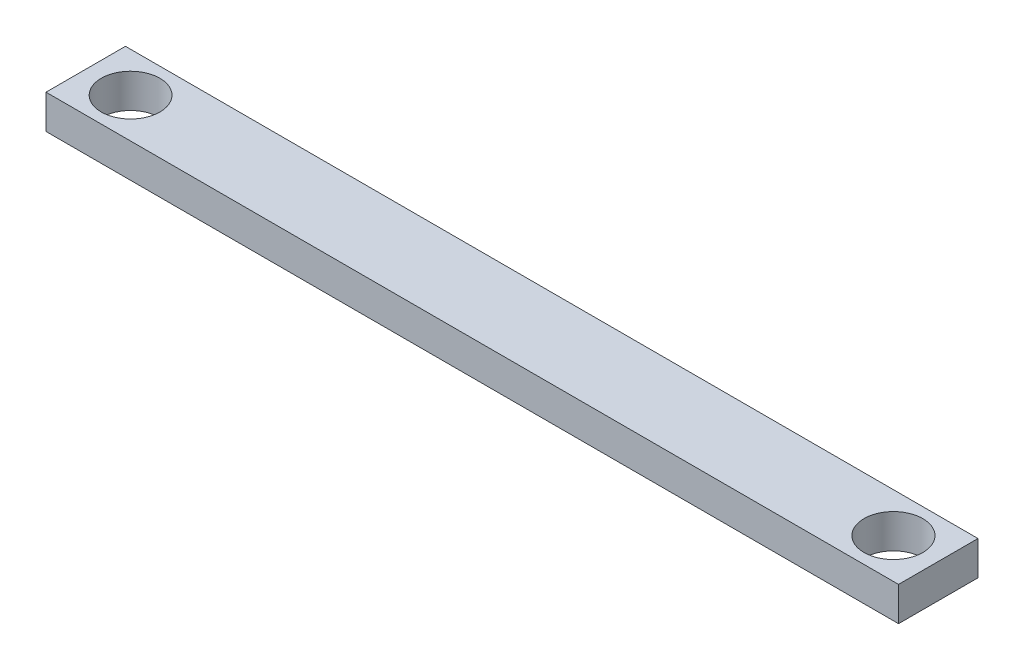
SolidWorks part; units mm, degrees
ref_plane "Front Plane" through (0, 0, 0) normal (0, 0, 1) x (1, 0, 0)
ref_plane "Top Plane" through (0, 0, 0) normal (0, 1, 0) x (1, 0, 0)
ref_plane "Right Plane" through (0, 0, 0) normal (1, 0, 0) x (0, 0, -1)
sketch "Sketch1" plane through (0, 0, 0) normal (0, 1, 0) x (1, 0, 0)
  line L0 (-47.6, 1) -> (27.5, 1) construction
  line L1 (-47.6, -2.5) -> (27.5, -2.5)
  line L2 (-47.6, -2.5) -> (-47.6, 4.5)
  line L3 (-47.6, 4.5) -> (27.5, 4.5)
  line L4 (27.5, -2.5) -> (27.5, 4.5)
  line L7 (-10.05, 4.5) -> (-10.05, -2.5) construction
  line L8 (-43.65, 4.5) -> (-43.65, -2.5) construction
  line L9 (23.55, 4.5) -> (23.55, -2.5) construction
  circle A0 centre (-43.65, 1) radius 2.58
  circle A1 centre (23.55, 1) radius 2.59
  point P0 (0, 0)
  dimension "D1" = 75.1
  dimension "D2" = 7
  dimension "D3" = 67.2
  dimension "D4" = 33.6
extrude "Boss-Extrude1" add sketch "Sketch1" along normal blind 3
